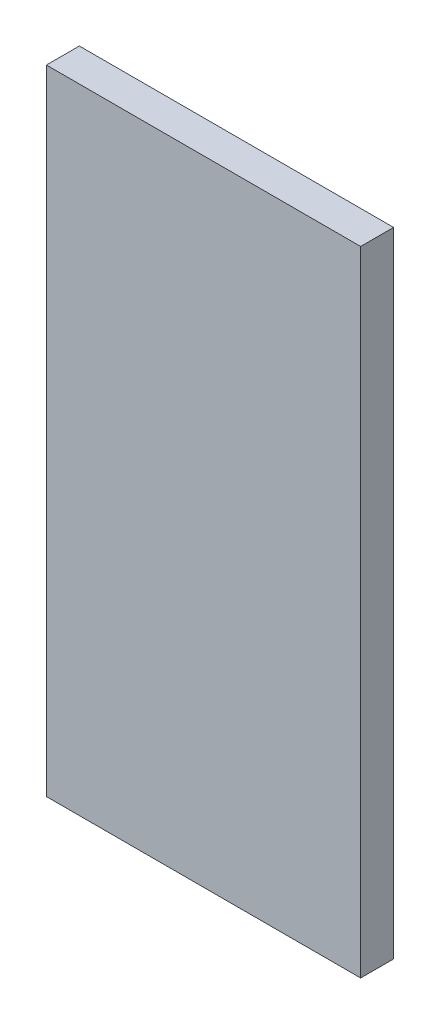
SolidWorks part; units mm, degrees
ref_plane "Piano frontale" through (0, 0, 0) normal (0, 0, 1) x (1, 0, 0)
ref_plane "Piano superiore" through (0, 0, 0) normal (0, 1, 0) x (1, 0, 0)
ref_plane "Piano destro" through (0, 0, 0) normal (1, 0, 0) x (0, 0, -1)
sketch "Schizzo1" plane through (0, 0, 0) normal (0, 0, 1) x (1, 0, 0)
  line L1 (-31, 62.5) -> (31, 62.5)
  line L2 (-31, 62.5) -> (-31, -62.5)
  line L3 (-31, -62.5) -> (31, -62.5)
  line L4 (31, 62.5) -> (31, -62.5)
  line L5 (-31, 62.5) -> (31, -62.5) construction
  line L6 (-31, -62.5) -> (31, 62.5) construction
  point P0 (0, 0)
  dimension "D1" = 62
  dimension "D2" = 125
extrude "Estrusione-Estrusione1" add sketch "Schizzo1" along normal blind 6.5
